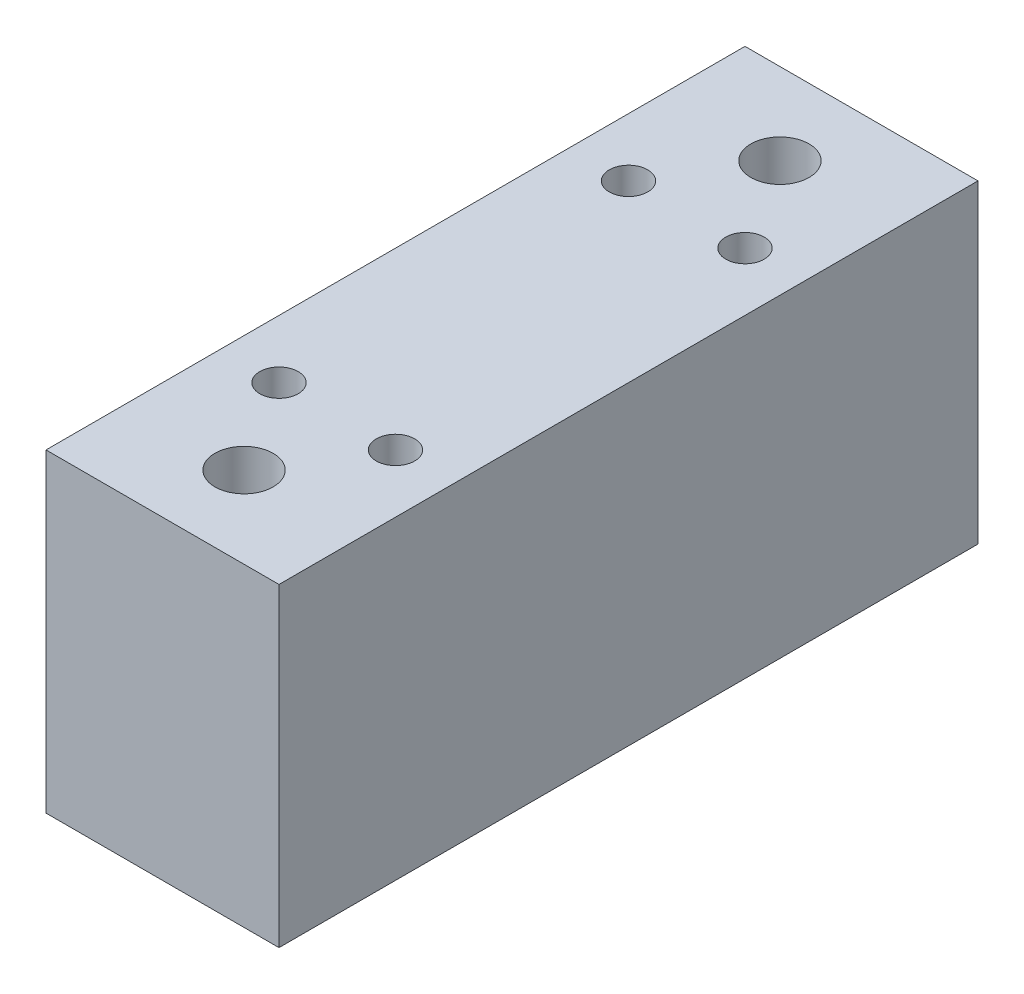
SolidWorks part; units mm, degrees
material "6061 Сплав"
ref_plane "Front" through (0, 0, 0) normal (0, 0, 1) x (1, 0, 0)
ref_plane "Top" through (0, 0, 0) normal (0, 1, 0) x (1, 0, 0)
ref_plane "Right" through (0, 0, 0) normal (1, 0, 0) x (0, 0, -1)
sketch "Эскиз1" plane through (0, 0, 0) normal (0, 0, 1) x (1, 0, 0)
  line L1 (-20, 13.5) -> (20, 13.5)
  line L2 (-20, 13.5) -> (-20, -13.5)
  line L3 (-20, -13.5) -> (20, -13.5)
  line L4 (20, 13.5) -> (20, -13.5)
  line L5 (-20, 13.5) -> (20, -13.5) construction
  line L6 (-20, -13.5) -> (20, 13.5) construction
  point P0 (0, 0)
  dimension "D1" = 27
  dimension "D2" = 40
extrude "Бобышка-Вытянуть1" add sketch "Эскиз1" along normal blind 60
sketch "Эскиз2" plane through (0, 13.5, 0) normal (0, 1, 0) x (1, 0, 0)
  line L0 (20, 0) -> (-20, 0) construction
  line L1 (-20, -60) -> (-20, 0) construction
  circle A0 centre (-10, -7) radius 2.5
  dimension "D1" = 7
  dimension "D2" = 10
extrude "Вырез-Вытянуть1" cut sketch "Эскиз2" against normal blind 27
pattern_linear "Линейный массив1" count 2 spacing 46 along (0, 0, 1) of "Вырез-Вытянуть1"
sketch "Эскиз4" plane through (0, 13.5, 0) normal (0, 1, 0) x (1, 0, 0)
  line L0 (20, -60) -> (-20, -60) construction
  line L1 (-20, -60) -> (-20, 0) construction
  circle A0 centre (-15, -15) radius 1.65
  circle A1 centre (-15, -45) radius 1.65
  dimension "D1" = 5
  dimension "D2" = 30
  dimension "D3" = 5
  dimension "D4" = 15
extrude "Вырез-Вытянуть3" cut sketch "Эскиз4" against normal blind 27
sketch "Эскиз5" plane through (0, -13.5, 0) normal (0, -1, 0) x (1, 0, 0)
  line L1 (20, 60) -> (0, 60)
  line L2 (20, 60) -> (20, 0)
  line L3 (20, 0) -> (0, 0)
  line L4 (0, 60) -> (0, 0)
extrude "Вырез-Вытянуть4" cut sketch "Эскиз5" against normal blind 30
pattern_linear "Линейный массив2" count 2 spacing 10 along (1, 0, 0) of "Вырез-Вытянуть3"
